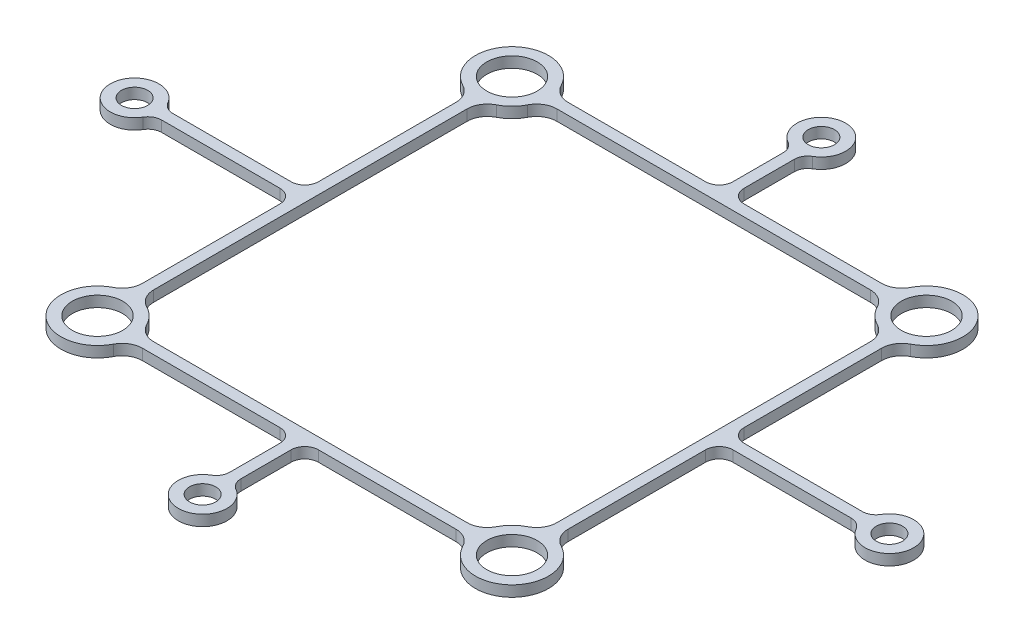
SolidWorks part; units mm, degrees
material "Custom Plastic"
ref_plane "Front Plane" through (0, 0, 0) normal (0, 0, 1) x (1, 0, 0)
ref_plane "Top Plane" through (0, 0, 0) normal (0, 1, 0) x (1, 0, 0)
ref_plane "Right Plane" through (0, 0, 0) normal (1, 0, 0) x (0, 0, -1)
sketch "Sketch1" plane through (0, 0, 0) normal (0, 1, 0) x (1, 0, 0)
  line L0 (0, 0) -> (0, 24.4542) construction
  line L1 (-30.445, -30.445) -> (30.445, -30.445) construction
  line L2 (-30.445, -30.445) -> (-30.445, 30.445) construction
  line L3 (-30.445, 30.445) -> (30.445, 30.445) construction
  line L4 (30.445, -30.445) -> (30.445, 30.445) construction
  line L5 (-30.445, -30.445) -> (30.445, 30.445) construction
  line L6 (-30.445, 30.445) -> (30.445, -30.445) construction
  line L7 (-21.3316, 0) -> (0, 0) construction
  line L8 (-25.1489, 31.27) -> (-0.825, 31.27)
  line L9 (-25.1489, 29.62) -> (25.1489, 29.62)
  line L10 (0, 30.445) -> (0, 45.445) construction
  line L11 (-0.825, 41.9665) -> (-0.825, 31.27)
  line L12 (0.825, 41.9665) -> (0.825, 31.27)
  line L13 (0.825, 31.27) -> (25.1489, 31.27)
  line L14 (0, -30.445) -> (0, -45.445) construction
  line L15 (-25.1489, -29.62) -> (25.1489, -29.62)
  line L16 (30.445, 0) -> (55.445, 0) construction
  line L17 (29.62, -25.1489) -> (29.62, 25.1489)
  line L18 (31.27, 25.1489) -> (31.27, 0.825)
  line L19 (0.825, -31.27) -> (25.1489, -31.27)
  line L20 (-25.1489, -31.27) -> (-0.825, -31.27)
  line L21 (0.825, -41.9665) -> (0.825, -31.27)
  line L22 (-0.825, -41.9665) -> (-0.825, -31.27)
  line L23 (31.27, -0.825) -> (51.9665, -0.825)
  line L24 (-34.155, 30.445) -> (-34.155, 88.2809) construction
  line L25 (34.155, 30.445) -> (34.155, 88.2809) construction
  line L26 (31.27, 0.825) -> (51.9665, 0.825)
  line L27 (31.27, -0.825) -> (31.27, -25.1489)
  line L28 (-30.445, 0) -> (-55.445, 0) construction
  line L29 (-31.27, -0.825) -> (-51.9665, -0.825)
  line L30 (-31.27, -0.825) -> (-31.27, -25.1489)
  line L31 (-31.27, 0.825) -> (-51.9665, 0.825)
  line L32 (-31.27, 25.1489) -> (-31.27, 0.825)
  line L33 (-29.62, -25.1489) -> (-29.62, 25.1489)
  arc A0 (-29.62, 25.1489) -> (-25.1489, 29.62) centre (-30.445, 30.445) ccw
  circle A1 centre (-30.445, 30.445) radius 3.71
  circle A2 centre (30.445, 30.445) radius 3.71
  arc A3 (25.1489, 31.27) -> (31.27, 25.1489) centre (30.445, 30.445) cw
  arc A4 (29.62, -25.1489) -> (25.1489, -29.62) centre (30.445, -30.445) ccw
  circle A5 centre (30.445, -30.445) radius 3.71
  arc A6 (-25.1489, -31.27) -> (-31.27, -25.1489) centre (-30.445, -30.445) cw
  circle A7 centre (-30.445, -30.445) radius 3.71
  circle A8 centre (0, 45.445) radius 1.925
  arc A9 (0.825, 41.9665) -> (-0.825, 41.9665) centre (0, 45.445) ccw
  circle A10 centre (55.445, 0) radius 1.925
  arc A11 (51.9665, -0.825) -> (51.9665, 0.825) centre (55.445, 0) ccw
  circle A12 centre (0, -45.445) radius 1.925
  arc A13 (0.825, -41.9665) -> (-0.825, -41.9665) centre (0, -45.445) cw
  circle A14 centre (-55.445, 0) radius 1.925
  arc A15 (-51.9665, -0.825) -> (-51.9665, 0.825) centre (-55.445, 0) cw
  arc A16 (-25.1489, 31.27) -> (-31.27, 25.1489) centre (-30.445, 30.445) ccw
  arc A18 (29.62, 25.1489) -> (25.1489, 29.62) centre (30.445, 30.445) cw
  arc A20 (25.1489, -31.27) -> (31.27, -25.1489) centre (30.445, -30.445) ccw
  arc A22 (-29.62, -25.1489) -> (-25.1489, -29.62) centre (-30.445, -30.445) cw
  point P0 (0, 0)
  dimension "D1" = 1.65
  dimension "D2" = 15
  dimension "D5" = 7.42
  dimension "D6" = 3.85
  dimension "D8" = 1.65
  dimension "D12" = 0.825
  dimension "D13" = 3.85
  dimension "D14" = 1.65
  dimension "D3" = 0.825
  dimension "D4" = 0.825
  dimension "D7" = 68.31
  dimension "D9" = 0.825
  dimension "D10" = 0.825
  dimension "D11" = 0.825
  dimension "D15" = 0.825
  dimension "D16" = 0.825
  dimension "D17" = 25
extrude "Boss-Extrude1" add sketch "Sketch1" along normal blind 1.5875
fillet "Fillet1" radius 3 16 edges at (-25.1489, 0.7937, 31.27) (-25.1489, 0.7937, 29.62) (-29.62, 0.7937, 25.1489) (-31.27, 0.7937, 25.1489) (31.27, 0.7937, 25.1489) (29.62, 0.7937, 25.1489) (25.1489, 0.7937, 29.62) (25.1489, 0.7937, 31.27) (25.1489, 0.7937, -31.27) (25.1489, 0.7937, -29.62) (29.62, 0.7937, -25.1489) (31.27, 0.7937, -25.1489) (-25.1489, 0.7937, -31.27) (-31.27, 0.7937, -25.1489) (-29.62, 0.7937, -25.1489) (-25.1489, 0.7937, -29.62)
fillet "Fillet2" radius 2 8 edges at (0.825, 0.7937, -31.27) (-0.825, 0.7937, -31.27) (-31.27, 0.7937, 0.825) (-31.27, 0.7937, -0.825) (-0.825, 0.7937, 31.27) (0.825, 0.7937, 31.27) (31.27, 0.7937, 0.825) (31.27, 0.7937, -0.825)
fillet "Fillet3" radius 2 8 edges at (-0.825, 0.7937, -41.9665) (0.825, 0.7937, -41.9665) (-51.9665, 0.7937, 0.825) (-51.9665, 0.7937, -0.825) (51.9665, 0.7937, 0.825) (51.9665, 0.7937, -0.825) (-0.825, 0.7937, 41.9665) (0.825, 0.7937, 41.9665)
